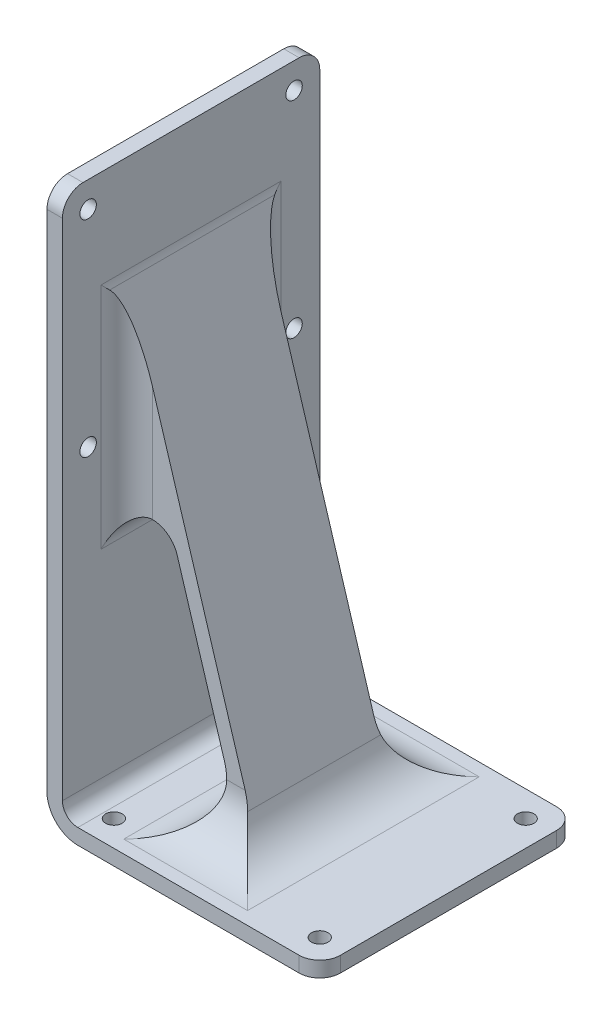
SolidWorks part; units mm, degrees
ref_plane "Front Plane" through (0, 0, 0) normal (0, 0, 1) x (1, 0, 0)
ref_plane "Top Plane" through (0, 0, 0) normal (0, 1, 0) x (1, 0, 0)
ref_plane "Right Plane" through (0, 0, 0) normal (1, 0, 0) x (0, 0, -1)
sketch "Sketch2" plane through (0, 0, 0) normal (0, 1, 0) x (1, 0, 0)
  line L1 (-25, -25) -> (25, -25)
  line L2 (-25, -25) -> (-25, 25)
  line L3 (-25, 25) -> (25, 25)
  line L4 (25, -25) -> (25, 25)
  line L5 (-25, -25) -> (25, 25) construction
  line L6 (-25, 25) -> (25, -25) construction
  point P0 (0, 0)
  dimension "D1" = 50
  dimension "D2" = 50
extrude "Boss-Extrude1" add sketch "Sketch2" along normal blind 3
sketch "Sketch3" plane through (0, 3, 0) normal (0, 1, 0) x (1, 0, 0)
  line L1 (-20, -20) -> (20, -20) construction
  line L2 (-20, -20) -> (-20, 20) construction
  line L3 (-20, 20) -> (20, 20) construction
  line L4 (20, -20) -> (20, 20) construction
  line L5 (-20, -20) -> (20, 20) construction
  line L6 (-20, 20) -> (20, -20) construction
  circle A0 centre (-20, 20) radius 1.6
  circle A1 centre (20, 20) radius 1.6
  circle A2 centre (-20, -20) radius 1.6
  circle A3 centre (20, -20) radius 1.6
  point P1 (0, 0)
  dimension "D2" = 3.2
  dimension "D1" = 40
extrude "Cut-Extrude1" cut sketch "Sketch3" against normal up to surface (3 mm away) up to face at (0, 0, 0)
fillet "Fillet1" radius 4 2 edges at (25, 1.5, -25) (25, 1.5, 25)
sketch "Sketch4" plane through (-25, 0, 0) normal (-1, 0, 0) x (0, 0, 1)
  line L0 (-25, 3) -> (-25, 0) construction
  line L1 (25, 3) -> (25, 0) construction
  line L2 (-25, 0) -> (25, 0) construction
  line L3 (-25, 3) -> (25, 3) construction
  line L4 (-25, 3) -> (-25, 0)
  line L5 (25, 3) -> (25, 0)
  line L6 (-25, 0) -> (25, 0)
  line L7 (-25, 3) -> (25, 3)
extrude "Boss-Extrude2" add sketch "Sketch4" along normal blind 3
sketch "Sketch5" plane through (0, 3, 0) normal (0, 1, 0) x (1, 0, 0)
  line L0 (21, 25) -> (-28, 25) construction
  line L1 (-28, -25) -> (-25, -25)
  line L2 (-28, -25) -> (-28, 25)
  line L3 (-28, 25) -> (-25, 25)
  line L4 (-25, -25) -> (-25, 25)
  dimension "D1" = 3
extrude "Boss-Extrude3" add sketch "Sketch5" along normal blind 55
sketch "Sketch6" plane through (0, 58, 0) normal (0, 1, 0) x (1, 0, 0)
  line L1 (-28, 25) -> (-25, 25)
  line L2 (-28, 25) -> (-28, -25)
  line L3 (-28, -25) -> (-25, -25)
  line L4 (-25, 25) -> (-25, -25)
extrude "Boss-Extrude4" add sketch "Sketch6" along normal blind 50
sketch "Sketch7" plane through (-25, 0, 0) normal (1, 0, 0) x (0, 0, -1)
  line L0 (-20, 103) -> (-18.8686, 101.8686) construction
  line L1 (-20, 63) -> (20, 63) construction
  line L2 (-20, 63) -> (-20, 103) construction
  line L3 (-20, 103) -> (20, 103) construction
  line L4 (20, 63) -> (20, 103) construction
  line L5 (-25, 108) -> (25, 108) construction
  line L6 (-25, 108) -> (-25, 3) construction
  line L7 (-25, 58) -> (25, 58) construction
  line L8 (-25, 58) -> (-25, 108) construction
  line L9 (-25, 108) -> (25, 108) construction
  line L10 (25, 58) -> (25, 108) construction
  line L11 (25, 108) -> (25, 3) construction
  line L12 (20, 103) -> (18.8686, 101.8686) construction
  line L13 (-18.8686, 64.1314) -> (-20, 63) construction
  line L14 (18.8686, 64.1314) -> (20, 63) construction
  circle A0 centre (-20, 63) radius 1.6
  circle A1 centre (-20, 103) radius 1.6
  circle A2 centre (20, 103) radius 1.6
  circle A3 centre (20, 63) radius 1.6
  point P6 (0, 108)
  point P7 (0, 103)
  point P16 (-25, 83)
  point P17 (-20, 83)
  dimension "D3" = 3.2
  dimension "D1" = 40
  dimension "D2" = 40
extrude "Cut-Extrude2" cut sketch "Sketch7" against normal up to surface (3 mm away) up to face at (-28, 54, 0)
fillet "Fillet2" radius 4 2 edges at (-26.5, 108, -25) (-26.5, 108, 25)
fillet "Fillet3" radius 3 1 edges at (-25, 3, 0)
fillet "Fillet4" radius 6 1 edges at (-28, 0, 0)
sketch "Sketch8" plane through (0, 0, 0) normal (0, 0, 1) x (1, 0, 0)
  line L0 (-2.0685, 3) -> (1.0685, 3)
  line L1 (-22, 3) -> (21, 3) construction
  line L2 (1.0685, 3) -> (-25, 88.2663)
  line L3 (-25, 104) -> (-25, 6) construction
  line L4 (-25, 88.2663) -> (-25, 78.0054)
  line L5 (-25, 78.0054) -> (-2.0685, 3)
  point P0 (-0.5, 3)
  point P4 (-0.5, 3)
  dimension "D1" = 107
  dimension "D2" = 3
extrude "Boss-Extrude5" add sketch "Sketch8" along normal mid plane 25
fillet "Fillet5" radius 5 4 edges at (-25, 78.0054, 0) (-25, 83.1359, 12.5) (-25, 83.1359, -12.5) (-25, 88.2663, 0)
fillet "Fillet6" radius 10 4 edges at (-0.5, 3, 12.5) (-2.0685, 3, 0) (-0.5, 3, -12.5) (1.0685, 3, 0)
